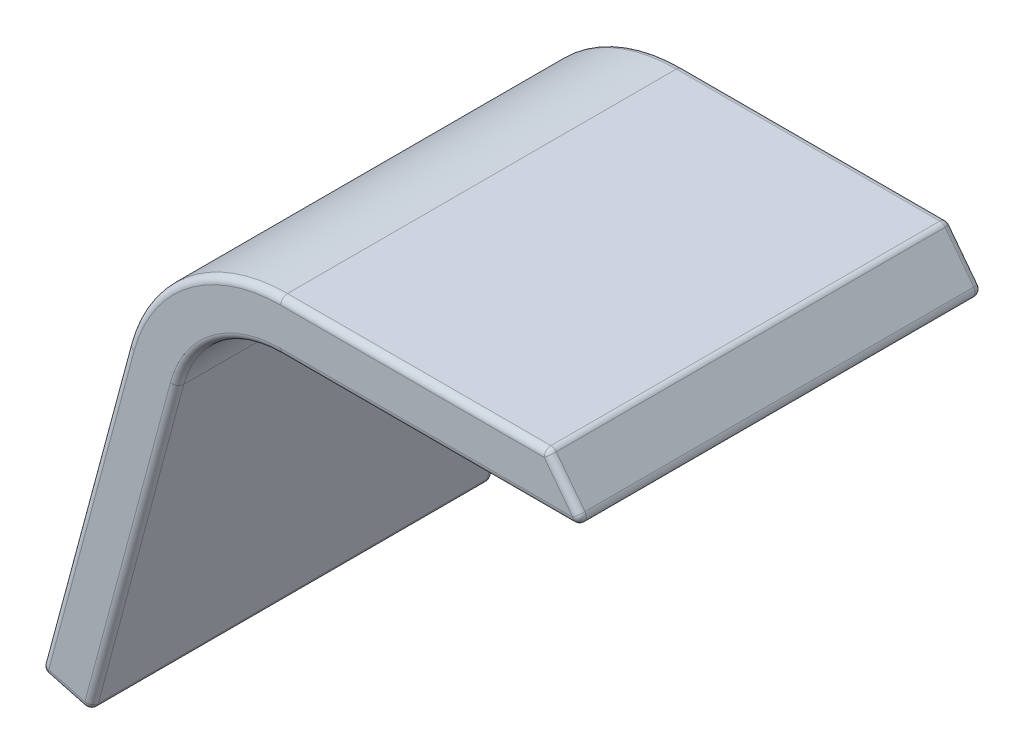
SolidWorks part; units mm, degrees
ref_plane "Front Plane" through (0, 0, 0) normal (0, 0, 1) x (1, 0, 0)
ref_plane "Top Plane" through (0, 0, 0) normal (0, 1, 0) x (1, 0, 0)
ref_plane "Right Plane" through (0, 0, 0) normal (1, 0, 0) x (0, 0, -1)
sketch "Sketch1" plane through (0, 0, 0) normal (0, 0, 1) x (1, 0, 0)
  line L0 (-225, 0) -> (225, 0)
  line L1 (225, 0) -> (167.4505, 75)
  line L2 (167.4505, 75) -> (-225, 75)
  line L3 (-225, 75) -> (-225, 0)
  line L4 (-225, -158) -> (-450.0607, -97.6952) construction
  line L5 (-225, -158) -> (-225, 0) construction
  line L6 (-450.0607, -97.6952) -> (-377.6163, -117.1066)
  line L7 (-450.0607, -97.6952) -> (-578.435, -576.7944)
  line L8 (-578.435, -576.7944) -> (-505.9905, -596.2058)
  line L9 (-505.9905, -596.2058) -> (-377.6163, -117.1066)
  arc A0 (-225, 0) -> (-377.6163, -117.1066) centre (-225, -158) ccw
  arc A1 (-225, 75) -> (-450.0607, -97.6952) centre (-225, -158) ccw
  point P3 (0, 0)
  dimension "D6" = 158
  dimension "D1" = 75
  dimension "D2" = 52.5
  dimension "D3" = 450
  dimension "D4" = 158
  dimension "D5" = 75
  dimension "D7" = 496
extrude "Boss-Extrude1" add sketch "Sketch1" along normal mid plane 592 contours L3 A1 L6 A0 | L2 L3 L0 L1 | L8 L9 L6 L7
fillet "Fillet1" radius 10 20 edges at (225, 0, 0) (167.4505, 75, 0) (-321.1843, -32.6502, -296) (-321.1843, -32.6502, 296) (-366.8414, 26.8513, -296) (-366.8414, 26.8513, 296) (0, 0, -296) (0, 0, 296) (196.2252, 37.5, -296) (196.2252, 37.5, 296) (-28.7748, 75, -296) (-28.7748, 75, 296) (-441.8034, -356.6562, -296) (-441.8034, -356.6562, 296) (-514.2478, -337.2448, -296) (-514.2478, -337.2448, 296) (-578.435, -576.7944, 0) (-542.2127, -586.5001, -296) (-542.2127, -586.5001, 296) (-505.9905, -596.2058, 0)
